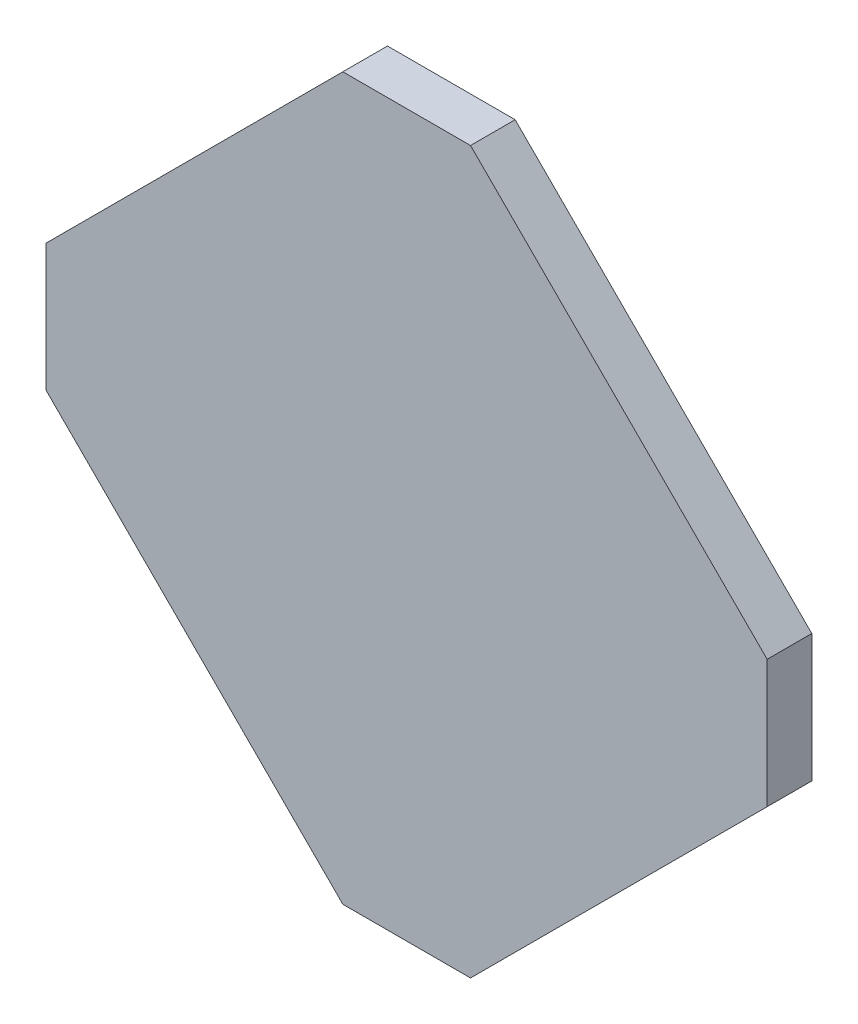
SolidWorks part; units mm, degrees
ref_plane "前视基准面" through (0, 0, 0) normal (0, 0, 1) x (1, 0, 0)
ref_plane "上视基准面" through (0, 0, 0) normal (0, 1, 0) x (1, 0, 0)
ref_plane "右视基准面" through (0, 0, 0) normal (1, 0, 0) x (0, 0, -1)
sketch "草图1" plane through (0, 0, 0) normal (0, 0, 1) x (1, 0, 0)
  line L0 (-94.9643, 29.5521) -> (2.369, 29.5521) construction
  line L1 (24.3333, 73) -> (121.6667, 73) construction
  line L2 (41.4695, 98.4139) -> (1.5995, 58.544)
  line L3 (1.5995, 58.544) -> (1.5995, 41.3826)
  line L4 (1.5995, 41.3826) -> (41.4695, 1.5126)
  line L5 (41.4695, 1.5126) -> (58.6309, 1.5126)
  line L6 (58.6309, 1.5126) -> (98.5009, 41.3826)
  line L7 (98.5009, 41.3826) -> (98.5009, 58.544)
  line L8 (98.5009, 58.544) -> (58.6309, 98.4139)
  line L9 (58.6309, 98.4139) -> (41.4695, 98.4139)
  line L10 (43.1264, 94.4139) -> (5.5995, 56.8871)
  line L11 (5.5995, 56.8871) -> (5.5995, 43.0394)
  line L12 (5.5995, 43.0394) -> (43.1264, 5.5126)
  line L13 (43.1264, 5.5126) -> (56.9741, 5.5126)
  line L14 (56.9741, 5.5126) -> (94.5009, 43.0394)
  line L15 (94.5009, 43.0394) -> (94.5009, 56.8871)
  line L16 (94.5009, 56.8871) -> (56.9741, 94.4139)
  line L17 (56.9741, 94.4139) -> (43.1264, 94.4139)
  point P20 (0, 0)
  dimension "D1" = 4
extrude "凸台-拉伸1" add sketch "草图1" against normal blind 6
sketch "草图3" plane through (0, 0, 0) normal (0, 0, 1) x (1, 0, 0)
  line L0 (43.1264, 94.4139) -> (5.5995, 56.8871)
  line L1 (5.5995, 56.8871) -> (5.5995, 43.0394)
  line L2 (5.5995, 43.0394) -> (43.1264, 5.5126)
  line L3 (43.1264, 5.5126) -> (56.9741, 5.5126)
  line L4 (56.9741, 5.5126) -> (94.5009, 43.0394)
  line L5 (94.5009, 43.0394) -> (94.5009, 56.8871)
  line L6 (94.5009, 56.8871) -> (56.9741, 94.4139)
  line L7 (56.9741, 94.4139) -> (43.1264, 94.4139)
extrude "凸台-拉伸2" add sketch "草图3" against normal blind 2
sketch "草图4" plane through (0, 0, -2) normal (0, 0, -1) x (-1, 0, 0)
  line L0 (-26.673, 208.4663) -> (238.6603, 208.4663) construction
  line L1 (-83.125, 31.6636) -> (-66.5841, 31.6636)
  line L2 (-56.9741, 5.5126) -> (-94.5009, 43.0394) construction
  line L3 (-69.4854, 25.5569) -> (-64.9773, 30.0522)
  line L4 (-66.5841, 31.6636) -> (-64.9773, 30.0522)
  line L5 (-69.4854, 25.5569) -> (-57.7676, 12.9109)
  line L6 (-57.7676, 12.9109) -> (-35.7281, 12.9109)
  line L7 (-5.5995, 43.0394) -> (-43.1264, 5.5126) construction
  line L8 (-35.7281, 12.9109) -> (-24.7855, 23.8535)
  line L9 (-24.7855, 23.8535) -> (-54.3393, 23.8535)
  line L11 (-94.5009, 51.792) -> (-45.0814, 51.792)
  line L12 (-54.3393, 23.8535) -> (-67.682, 36.9479)
  line L13 (-67.682, 36.9479) -> (-56.3466, 48.4981)
  line L14 (-56.3466, 48.4981) -> (-5.5995, 48.4981)
  line L15 (-5.5995, 56.8871) -> (-5.5995, 43.0394) construction
  line L16 (-94.5009, 43.0394) -> (-94.5009, 56.8871) construction
  line L17 (-74.8859, 76.5021) -> (-43.434, 76.5021)
  line L18 (-94.5009, 56.8871) -> (-56.9741, 94.4139) construction
  line L19 (-31.9183, 64.7369) -> (-45.0814, 51.792)
  line L20 (-43.434, 76.5021) -> (-31.9183, 64.7369)
  line L21 (-74.8859, 76.5021) -> (-94.5009, 56.8871)
  line L22 (-94.5009, 56.8871) -> (-94.5009, 51.792)
  line L23 (-56.9741, 94.4139) -> (-63.9301, 87.4579)
  line L24 (-63.9301, 87.4579) -> (-43.0306, 87.4579)
  line L25 (-43.0306, 87.4579) -> (-31.0445, 74.652)
  line L26 (-31.0445, 74.652) -> (-35.0919, 70.8637)
  line L27 (-35.0919, 70.8637) -> (-33.3399, 68.9919)
  line L28 (-33.3399, 68.9919) -> (-17.7043, 68.9919)
  line L29 (-43.1264, 94.4139) -> (-5.5995, 56.8871) construction
  line L30 (-17.7043, 68.9919) -> (-43.1264, 94.4139)
  line L31 (-43.1264, 94.4139) -> (-56.9741, 94.4139)
  line L32 (-83.125, 31.6636) -> (-56.9741, 5.5126)
  line L33 (-56.9741, 5.5126) -> (-43.1264, 5.5126)
  line L34 (-43.1264, 5.5126) -> (-35.7281, 12.9109)
  line L35 (-74.8859, 76.5021) -> (-94.5009, 56.8871)
  line M28 (-43.1264, 94.4139) -> (-56.9741, 94.4139)
  line M29 (-56.9741, 94.4139) -> (-94.5009, 56.8871)
  line M30 (-94.5009, 56.8871) -> (-94.5009, 43.0394)
  line M31 (-94.5009, 43.0394) -> (-56.9741, 5.5126)
  line M32 (-56.9741, 5.5126) -> (-43.1264, 5.5126)
  line M33 (-43.1264, 5.5126) -> (-5.5995, 43.0394)
  line M34 (-5.5995, 43.0394) -> (-5.5995, 56.8871)
  line M35 (-5.5995, 56.8871) -> (-43.1264, 94.4139)
extrude "切除-拉伸1" cut sketch "草图4" against normal blind 0.8 contours L20 L17 L11 L19 M29 M30 | L27 L28 L24 L25 L26 M35 M28 M29 | L14 L13 L12 L9 M33 M34 | L6 L5 L3 L4 L1 M31 M32 M33
